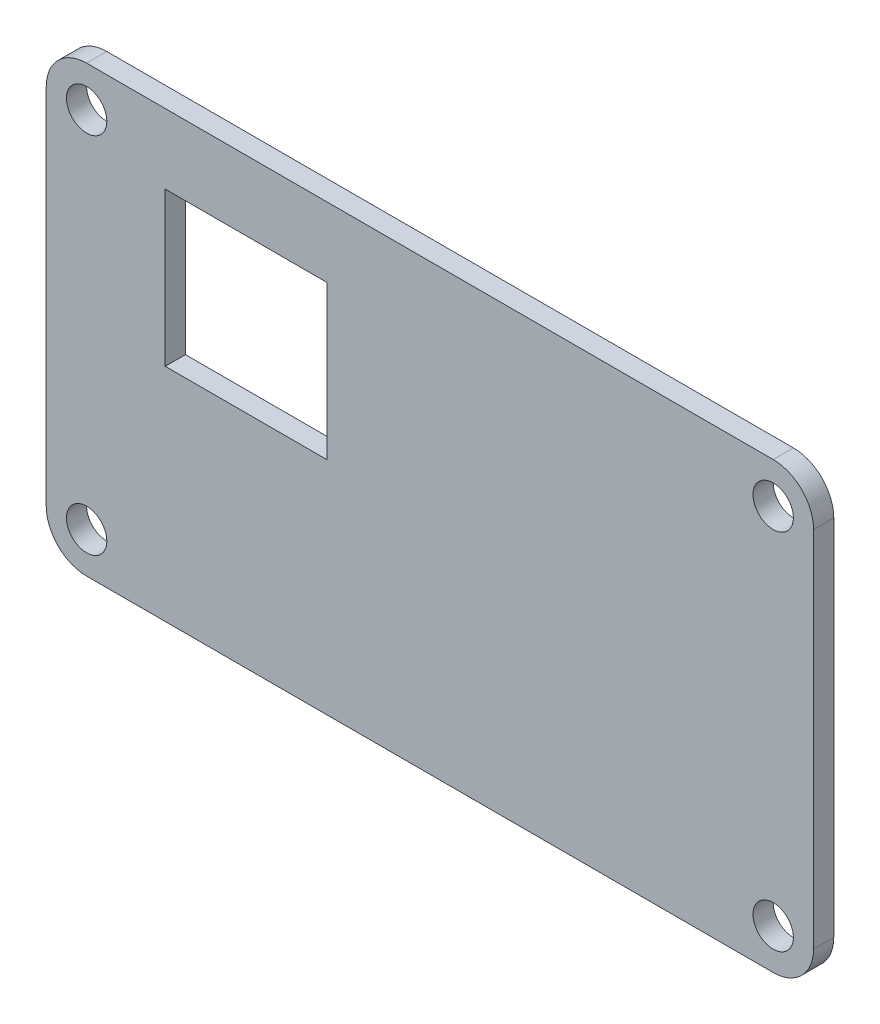
SolidWorks part; units mm, degrees
ref_plane "Front Plane" through (0, 0, 0) normal (0, 0, 1) x (1, 0, 0)
ref_plane "Top Plane" through (0, 0, 0) normal (0, 1, 0) x (1, 0, 0)
ref_plane "Right Plane" through (0, 0, 0) normal (1, 0, 0) x (0, 0, -1)
sketch "Sketch1" plane through (0, 0, 0) normal (0, 0, 1) x (1, 0, 0)
  line L1 (10, 0) -> (180, 0)
  line L2 (0, 10) -> (0, 100)
  line L3 (10, 110) -> (180, 110)
  line L4 (190, 10) -> (190, 100)
  arc A0 (190, 100) -> (180, 110) centre (180, 100) ccw
  arc A1 (190, 10) -> (180, 0) centre (180, 10) cw
  arc A2 (10, 0) -> (0, 10) centre (10, 10) cw
  arc A3 (10, 110) -> (0, 100) centre (10, 100) ccw
  point P9 (190, 0)
  point P12 (0, 0)
  point P15 (0, 110)
  dimension "D3" = 10
  dimension "D1" = 190
  dimension "D2" = 110
extrude "Boss-Extrude1" add sketch "Sketch1" along normal blind 5
sketch "Sketch2" plane through (0, 0, 0) normal (0, 0, -1) x (-1, 0, 0)
  circle A0 centre (-180, 100) radius 5
  circle A1 centre (-10, 100) radius 5
  circle A2 centre (-180, 10) radius 5
  circle A3 centre (-10, 10) radius 5
  point P0 (-100.665, 49.7675)
extrude "Cut-Extrude1" cut sketch "Sketch2" against normal blind 35
sketch "Sketch3" plane through (0, 0, 5) normal (0, 0, 1) x (1, 0, 0)
  line L1 (29.465, 54.7269) -> (69.465, 54.7269)
  line L2 (29.465, 54.7269) -> (29.465, 92.7269)
  line L3 (29.465, 92.7269) -> (69.465, 92.7269)
  line L4 (69.465, 54.7269) -> (69.465, 92.7269)
  dimension "D1" = 40
extrude "Cut-Extrude2" cut sketch "Sketch3" against normal blind 35
